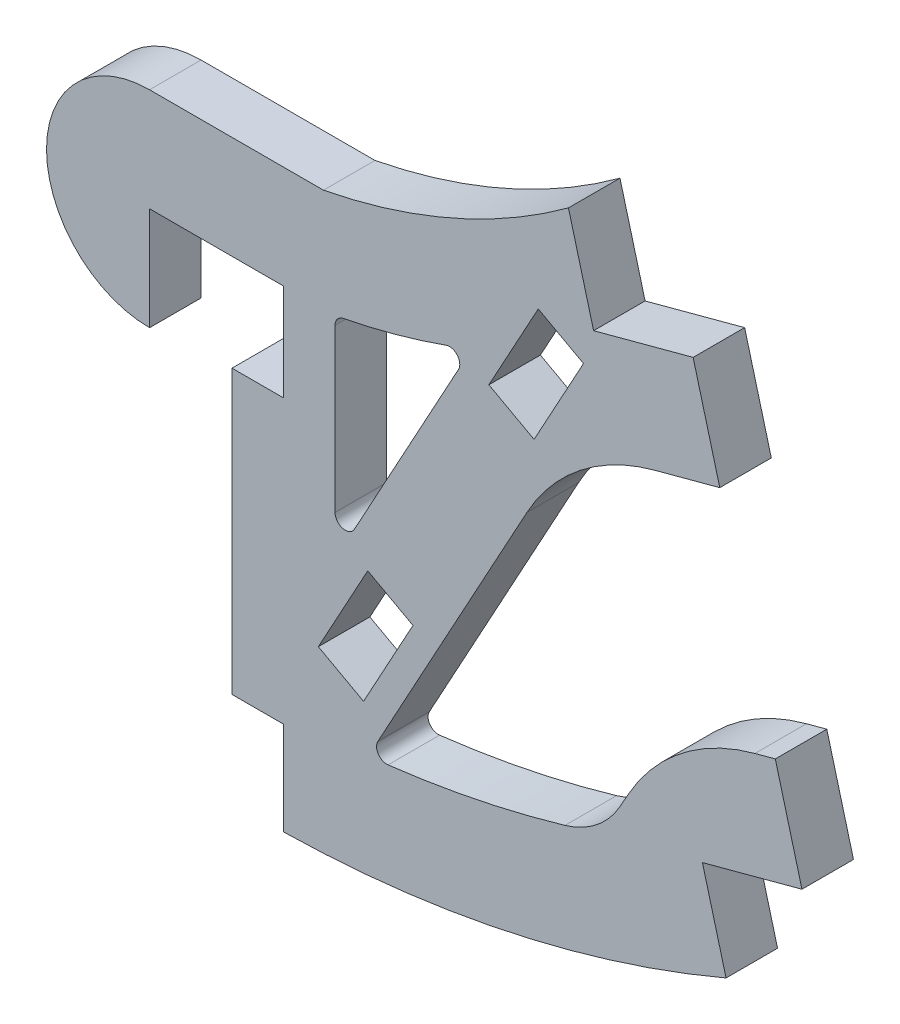
SolidWorks part; units mm, degrees
ref_plane "Front Plane" through (0, 0, 0) normal (0, 0, 1) x (1, 0, 0)
ref_plane "Top Plane" through (0, 0, 0) normal (0, 1, 0) x (1, 0, 0)
ref_plane "Right Plane" through (0, 0, 0) normal (1, 0, 0) x (0, 0, -1)
sketch "Sketch1" plane through (0, 0, 0) normal (0, 0, 1) x (1, 0, 0)
  line L0 (-13.8145, 55.753) -> (-0.5125, 55.753)
  line L1 (49.4852, 38.1) -> (-27.9551, 38.1) construction
  line L2 (-13.8145, 55.753) -> (-13.8145, 43.053)
  line L3 (40.9109, 70.0997) -> (37.8136, 81.6591)
  line L4 (-13.8145, 68.453) -> (7.6216, 68.453)
  line L5 (-13.8145, 68.453) -> (-0.5125, 68.453) construction
  line L6 (-13.8145, 55.753) -> (-13.8145, 45.593) construction
  line L7 (60.7961, 34.9162) -> (63.3061, 35.5888)
  line L8 (25.9067, 60.6532) -> (9.0455, 29.7963) construction
  line L9 (44.147, 20.9048) -> (45.2306, 22.8317)
  line L10 (49.4852, 38.1) -> (49.4852, 0.609) construction
  line L11 (49.4852, 0.609) -> (-0.4795, 0.609) construction
  line L12 (-3.6545, 43.8188) -> (2.6955, 43.8188)
  line L13 (57.2368, 9.1705) -> (57.2368, 19.0068) construction
  line L15 (24.2641, 57.647) -> (11.43, 34.16)
  line L16 (2.6955, 43.8188) -> (2.6955, 55.7568)
  line L17 (12.9488, 10.8032) -> (12.9488, 68.453) construction
  line L18 (9.0455, 34.769) -> (9.0455, 54.7452)
  line L20 (54.3258, 20.0345) -> (57.2368, 9.1705)
  line L21 (-3.6545, 8.9909) -> (-3.6545, 43.8188)
  line L22 (0.2488, -2.5395) -> (0.2488, 55.753) construction
  line L23 (12.9488, 68.453) -> (12.4434, 68.453) construction
  line L24 (12.4434, 68.453) -> (12.4434, 68.453) construction
  line L25 (12.4434, 68.453) -> (12.4434, 68.453) construction
  line L27 (40.9109, 70.0997) -> (54.3258, 20.0345) construction
  line L29 (48.4202, 58.9638) -> (56.4652, 61.1194)
  line L32 (32.7049, 46.6089) -> (14.3173, 12.9588)
  line L33 (42.4529, 64.4483) -> (15.3457, 14.8408) construction
  line L34 (-3.6545, 8.9909) -> (2.6955, 8.9909)
  line L35 (56.4652, 61.1194) -> (53.1782, 73.3867)
  line L36 (53.1782, 73.3867) -> (40.9109, 70.0997)
  line L38 (2.6955, 8.9909) -> (2.6955, -2.5123)
  line L39 (66.5931, 23.3215) -> (54.3258, 20.0345)
  line L40 (-13.8145, 45.593) -> (-20.32, 45.593) construction
  line L41 (0.2488, 55.753) -> (-13.8145, 55.753) construction
  line L42 (36.8806, 67.4932) -> (9.7734, 17.8857) construction
  line L43 (31.4791, 57.6083) -> (14.6179, 26.7514) construction
  line L44 (23.327, 42.6895) -> (28.8993, 39.6446) construction
  line L45 (33.5769, 54.8261) -> (28.0046, 57.871)
  line L46 (33.5769, 54.8261) -> (39.6667, 65.9708)
  line L47 (39.6667, 65.9708) -> (34.0944, 69.0157)
  line L48 (28.0046, 57.871) -> (34.0944, 69.0157)
  line L49 (33.5769, 54.8261) -> (34.0944, 69.0157) construction
  line L50 (39.6667, 65.9708) -> (28.0046, 57.871) construction
  line L51 (18.6494, 27.508) -> (13.077, 30.5529)
  line L52 (13.077, 30.5529) -> (6.9872, 19.4082)
  line L53 (12.5595, 16.3633) -> (6.9872, 19.4082)
  line L54 (18.6494, 27.508) -> (12.5595, 16.3633)
  line L58 (-0.5125, 55.753) -> (2.6955, 55.7568)
  line L60 (63.3061, 35.5888) -> (66.5931, 23.3215)
  arc A0 (7.6216, 68.453) -> (37.8136, 81.6591) centre (-6.8098, 142.5618) ccw
  arc A1 (0.2488, -2.5395) -> (77.5473, 19.7657) centre (-0.1558, 143.9537) ccw construction
  arc A2 (2.6955, -2.5123) -> (57.2368, 9.1705) centre (-0.1558, 143.9537) ccw
  arc A3 (-13.8145, 68.453) -> (-13.8145, 43.053) centre (-13.8145, 55.753) ccw
  arc A4 (6.7625, 68.2909) -> (21.1959, 72.4472) centre (-6.8098, 142.5618) ccw construction
  arc A5 (15.5812, 11.0886) -> (37.3919, 15.5366) centre (-0.1558, 143.9537) ccw
  arc A6 (44.147, 20.9048) -> (37.3919, 15.5366) centre (34.1842, 26.5073) cw
  arc A7 (10.0724, 55.9917) -> (22.7243, 59.4527) centre (-6.8098, 142.5618) ccw
  arc A8 (9.0455, 55.7978) -> (25.9067, 60.6532) centre (-6.8098, 142.5618) ccw construction
  arc A9 (12.9488, 10.8032) -> (70.8109, 30.5319) centre (-0.1558, 143.9537) ccw construction
  arc A10 (12.4434, 68.453) -> (12.4434, 68.453) centre (12.4434, 68.453) cw construction
  arc A11 (10.0724, 55.9917) -> (9.0455, 54.7452) centre (10.3155, 54.7452) ccw
  arc A12 (11.43, 34.16) -> (9.0455, 34.769) centre (10.3155, 34.769) cw
  arc A13 (0, 65.913) -> (-20.32, 45.593) centre (0, 45.593) ccw construction
  arc A14 (22.7243, 59.4527) -> (24.2641, 57.647) centre (23.1496, 58.256) cw
  arc A15 (15.5812, 11.0886) -> (14.3173, 12.9588) centre (15.4318, 12.3498) cw
  arc A16 (32.7049, 46.6089) -> (48.4202, 58.9638) centre (54.9942, 34.4293) cw
  arc A17 (45.2306, 22.8317) -> (60.7961, 34.9162) centre (67.3701, 10.3817) cw
  point P63 (33.8356, 61.9209)
  dimension "D15" = 6.35
  dimension "D4" = 11.43
  dimension "D5" = 1.27
  dimension "D6" = 25.4
  dimension "D7" = 25.4
  dimension "D3" = 38.1
  dimension "D9" = 12.7
  dimension "D16" = 12.7
  dimension "D17" = 12.7
  dimension "D18" = 6.35
  dimension "D20" = 6.35
  dimension "D12" = 6.35
  dimension "D13" = 12.7
  dimension "D21" = 12.7
extrude "Boss-Extrude1" add sketch "Sketch1" along normal blind 6.35
